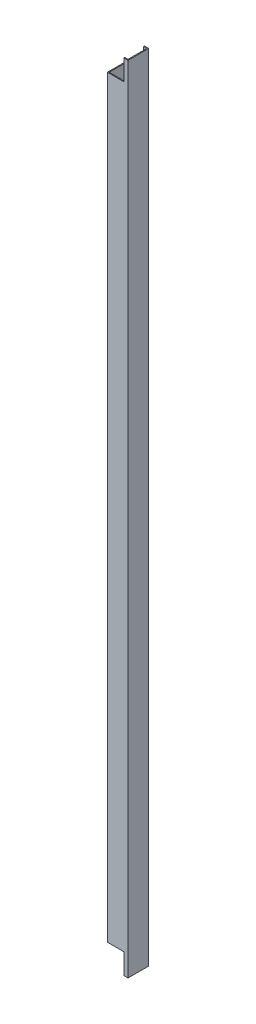
SolidWorks part; units mm, degrees
ref_plane "Front Plane" through (0, 0, 0) normal (0, 0, 1) x (1, 0, 0)
ref_plane "Top Plane" through (0, 0, 0) normal (0, 1, 0) x (1, 0, 0)
ref_plane "Right Plane" through (0, 0, 0) normal (1, 0, 0) x (0, 0, -1)
sketch "Sketch1" plane through (0, 0, 0) normal (0, 1, 0) x (1, 0, 0)
  line L0 (0, 0) -> (0, 50)
  line L1 (0, 50) -> (50, 50)
  line L2 (50, 50) -> (50, 0)
  line L3 (50, 0) -> (0, 0)
  line L4 (2.2, 47.8) -> (47.8, 47.8)
  line L5 (47.8, 47.8) -> (47.8, 2.2)
  line L6 (47.8, 2.2) -> (2.2, 2.2)
  line L7 (2.2, 2.2) -> (2.2, 47.8)
  dimension "D1" = 50
  dimension "D2" = 50
  dimension "D3" = 2.2
extrude "Boss-Extrude1" add sketch "Sketch1" along normal blind 1923
sketch "Sketch2" plane through (0, 0, 0) normal (0, 0, 1) x (1, 0, 0)
  line L0 (0, 0) -> (0, 50)
  line L1 (0, 1923) -> (0, 0) construction
  line L2 (0, 50) -> (40, 50)
  line L3 (40, 50) -> (40, 0)
  line L5 (40, 0) -> (0, 0)
  line L6 (0, 1923) -> (40, 1923)
  line L7 (0, 1923) -> (50, 1923) construction
  line L8 (40, 1923) -> (40, 1873)
  line L9 (40, 1873) -> (0, 1873)
  line L10 (0, 1873) -> (0, 1923)
  dimension "D1" = 50
  dimension "D2" = 40
  dimension "D3" = 50
  dimension "D4" = 40
extrude "Cut-Extrude2" cut sketch "Sketch2" against normal blind 50
equation "\"SquareTube_length\"=1923.0"
equation "\"D1@Boss-Extrude1\"=\"SquareTube_length\""
equation "\"SquareTube_inFront1_cutDepth50_R\"=0.5"
equation "\"D1@Sketch2\" = \"SquareTube_inFront7_cutDepth50_R\""
equation "\"SquareTube_inFront1_cutDepth50_L\"=0.5"
equation "\"D3@Sketch2\" = \"SquareTube_inFront7_cutDepth50_L\""
equation "\"CarBeamWidth\"=700.0"
equation "\"MetalSheet_3mm_length\"=5030.0"
equation "\"MetalSheet_3mm_width\"=1923.0"
equation "\"MetalSheet_3mm_FloorCut_L_length\"=1764.0"
equation "\"MetalSheet_3mm_FloorCut_L_disdance\"=1665.0"
equation "\"MetalSheet_3mm_FloorCut_R_length\"=1764.0"
equation "\"MetalSheet_3mm_FloorCut_R_disdance\"=1665.0"
equation "\"indoorHeight\"=1940.0"
equation "\"x\"=66.0"
equation "\"da\"=62.0"
equation "\"SquareTube_wheel_length\"= 750"
equation "\"channelSteel_length\"=5030.0"
equation "\"SquareTube_inFront2_cutDepth50_R\"=0.5"
equation "\"SquareTube_inFront2_cutDepth50_L\"=0.5"
equation "\"SquareTube_inFront3_cutDepth50_R\"=0.5"
equation "\"SquareTube_inFront3_cutDepth50_L\"=0.5"
equation "\"SquareTube_inFront4_cutDepth50_R\"=0.5"
equation "\"SquareTube_inFront4_cutDepth50_L\"=0.5"
equation "\"SquareTube_inFront5_cutDepth50_R\"=50"
equation "\"SquareTube_inFront5_cutDepth50_L\"=50"
equation "\"SquareTube_inFront6_cutDepth50_R\"=50"
equation "\"SquareTube_inFront6_cutDepth50_L\"=50"
equation "\"SquareTube_inFront7_cutDepth50_R\"=50"
equation "\"SquareTube_inFront7_cutDepth50_L\"=50"
equation "\"SquareTube_inFront8_cutDepth50_R\"=50"
equation "\"SquareTube_inFront8_cutDepth50_L\"=50"
equation "\"SquareTube_inFront9_cutDepth50_R\"=50"
equation "\"SquareTube_inFront9_cutDepth50_L\"=50"
equation "\"SquareTube_inFront10_cutDepth50_R\"=50"
equation "\"SquareTube_inFront10_cutDepth50_L\"=50"
equation "\"SquareTube_inBack1_cutDepth50_R\"=50"
equation "\"SquareTube_inBack1_cutDepth50_L\"=50"
equation "\"SquareTube_inBack2_cutDepth50_R\"=50"
equation "\"SquareTube_inBack2_cutDepth50_L\"=50"
equation "\"SquareTube_inBack3_cutDepth50_R\"=50"
equation "\"SquareTube_inBack3_cutDepth50_L\"=50"
equation "\"SquareTube_inBack4_cutDepth50_R\"=50"
equation "\"SquareTube_inBack4_cutDepth50_L\"=50"
equation "\"SquareTube_inBack5_cutDepth50_R\"=50"
equation "\"SquareTube_inBack5_cutDepth50_L\"=50"
equation "\"SquareTube_inBack6_cutDepth50_R\"=0.5"
equation "\"SquareTube_inBack6_cutDepth50_L\"=0.5"
